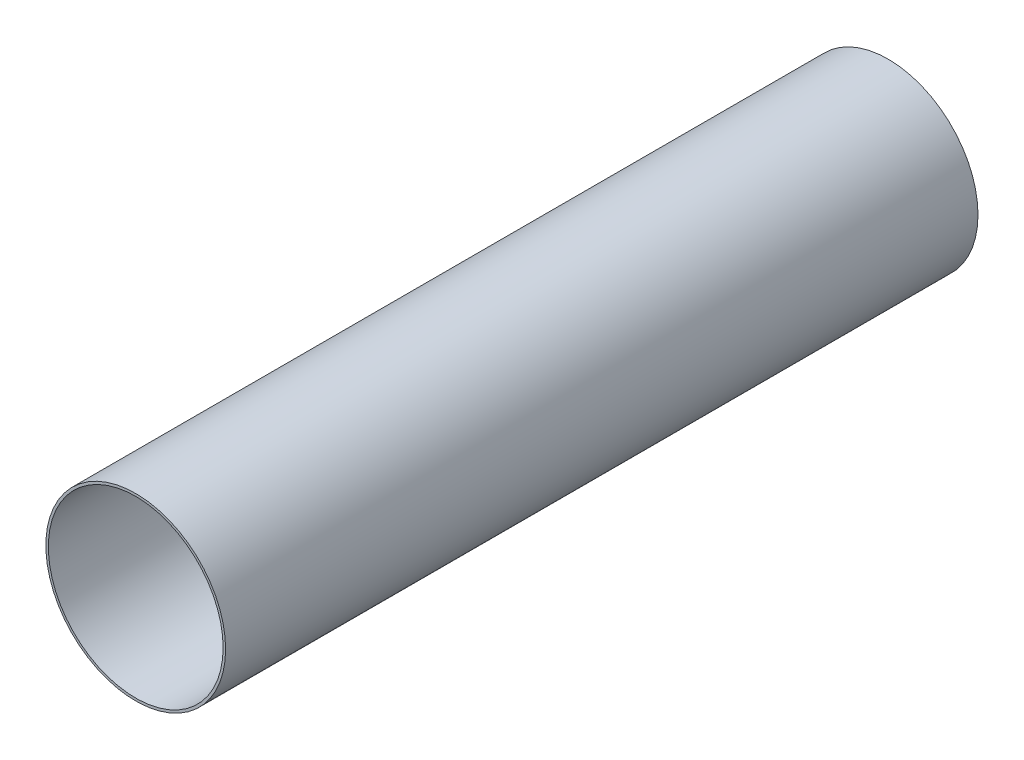
SolidWorks part; units mm, degrees
ref_plane "Front" through (0, 0, 0) normal (0, 0, 1) x (1, 0, 0)
ref_plane "Top" through (0, 0, 0) normal (0, 1, 0) x (1, 0, 0)
ref_plane "Right" through (0, 0, 0) normal (1, 0, 0) x (0, 0, -1)
sketch "Sketch1" plane through (0, 0, 0) normal (0, 0, 1) x (1, 0, 0)
  circle A0 centre (0, 0) radius 78.359
  circle A1 centre (0, 0) radius 76.2
  dimension "D1" = 156.718
  dimension "D2" = 152.4
extrude "Boss-Extrude1" add sketch "Sketch1" along normal blind 655.955
